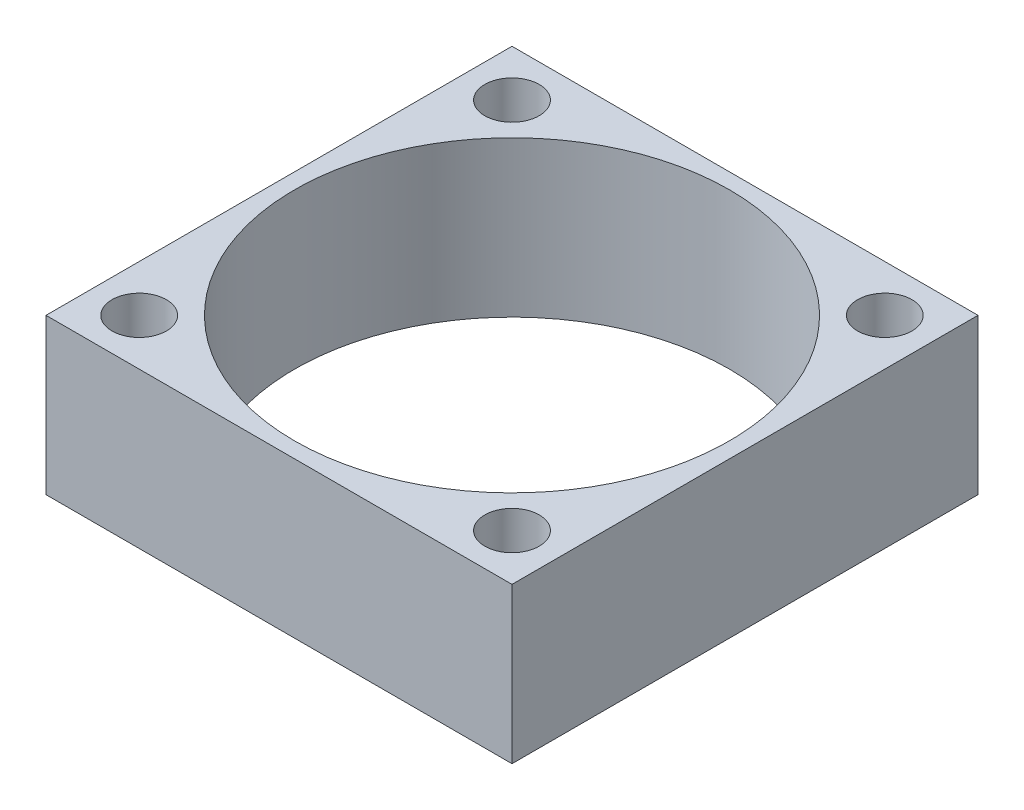
SolidWorks part; units mm, degrees
ref_plane "Спереди" through (0, 0, 0) normal (0, 0, 1) x (1, 0, 0)
ref_plane "Сверху" through (0, 0, 0) normal (0, 1, 0) x (1, 0, 0)
ref_plane "Справа" through (0, 0, 0) normal (1, 0, 0) x (0, 0, -1)
sketch "Эскиз1" plane through (0, 0, 0) normal (0, 1, 0) x (1, 0, 0)
  line L1 (0, 0) -> (30, 0)
  line L2 (0, 0) -> (0, 30)
  line L3 (0, 30) -> (30, 30)
  line L4 (30, 0) -> (30, 30)
  circle A0 centre (15, 15) radius 14
extrude "Бобышка-Вытянуть1" add sketch "Эскиз1" along normal blind 10
hole_wizard "Диаметр отверстия Ø3.5 (3.5)1" positions "Эскиз2" profile "Эскиз3" hole size "Ø3.5" standard "ISO" end condition through all
sketch "Эскиз2" plane through (0, 10, 0) normal (0, 1, 0) x (1, 0, 0)
  line L0 (30, 30) -> (0, 30) construction
  line L1 (0, 30) -> (0, 0) construction
  line L2 (0, 0) -> (30, 0) construction
  line L3 (30, 0) -> (30, 30) construction
  point P0 (3, 27)
  point P2 (27, 27)
  point P4 (27, 3)
  point P6 (3, 3)
  point P13 (0, 0)
  dimension "D1" = 3
  dimension "D2" = 3
  dimension "D3" = 3
  dimension "D4" = 3
  dimension "D5" = 3
  dimension "D6" = 3
  dimension "D7" = 3
  dimension "D8" = 3
sketch "Эскиз3" plane through (3, 10, -27) normal (1, 0, 0) x (0, 0, 1)
  line L0 (0, 0) -> (0, 10)
  line L1 (0, 10) -> (1.75, 10)
  line L2 (1.75, 10) -> (1.75, 0)
  line L5 (1.75, 0) -> (0, 0)
  line L11 (0, -6.35) -> (0, 107.95) construction
  dimension "Диаметр сквозного отверстия" = 3.5
  dimension "Глубина сквозного отверстия" = 10
